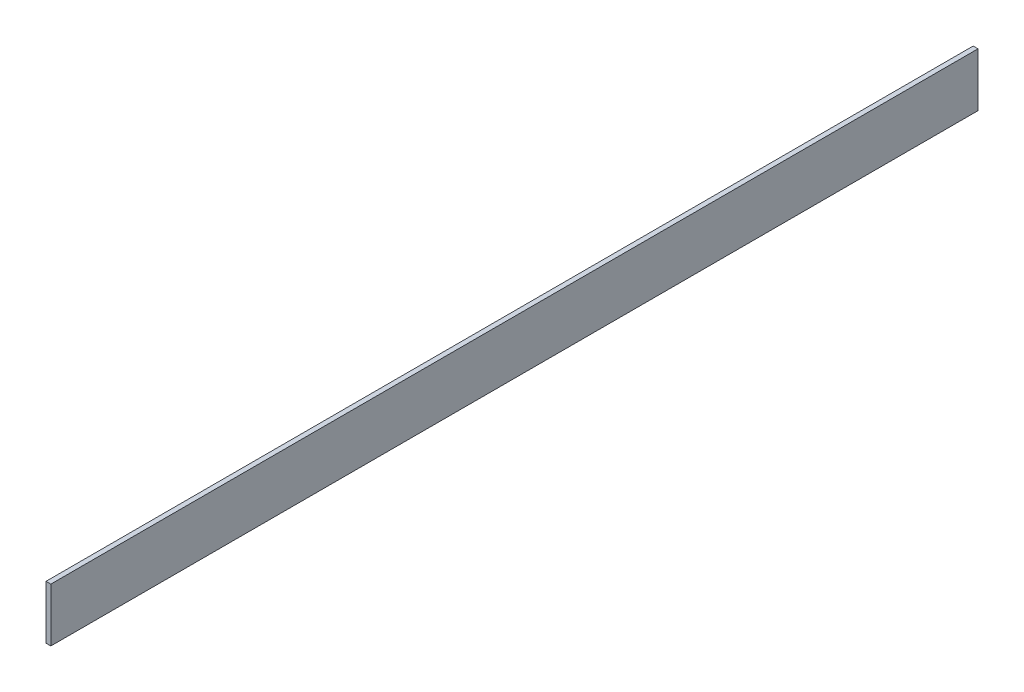
SolidWorks part; units mm, degrees
material "PC High Viscosity"
ref_plane "Front Plane" through (0, 0, 0) normal (0, 0, 1) x (1, 0, 0)
ref_plane "Top Plane" through (0, 0, 0) normal (0, 1, 0) x (1, 0, 0)
ref_plane "Right Plane" through (0, 0, 0) normal (1, 0, 0) x (0, 0, -1)
sketch "Sketch1" plane through (0, 0, 0) normal (1, 0, 0) x (0, 0, -1)
  line L1 (-609.6, 0) -> (609.6, 0)
  line L2 (-609.6, 0) -> (-609.6, 70.485)
  line L3 (-609.6, 70.485) -> (609.6, 70.485)
  line L4 (609.6, 0) -> (609.6, 70.485)
  dimension "D1" = 1219.2
  dimension "D2" = 70.485
extrude "Boss-Extrude1" add sketch "Sketch1" along normal blind 6.35
sketch "Sketch4" plane through (6.35, 0, 0) normal (1, 0, 0) x (0, 0, -1)
  line L0 (0, 0) -> (0, 70.485) construction
  line L1 (-609.6, 0) -> (-571.5, 0)
  line L2 (-609.6, 0) -> (-609.6, 20.32)
  line L3 (-609.6, 20.32) -> (-571.5, 20.32)
  line L4 (-571.5, 0) -> (-571.5, 20.32)
  line L5 (-609.6, 0) -> (609.6, 0) construction
  line L6 (609.6, 70.485) -> (-609.6, 70.485) construction
  line L7 (571.5, 0) -> (571.5, 20.32)
  line L8 (609.6, 20.32) -> (571.5, 20.32)
  line L9 (609.6, 0) -> (609.6, 20.32)
  line L10 (609.6, 0) -> (571.5, 0)
  dimension "D1" = 38.1
  dimension "D2" = 20.32
